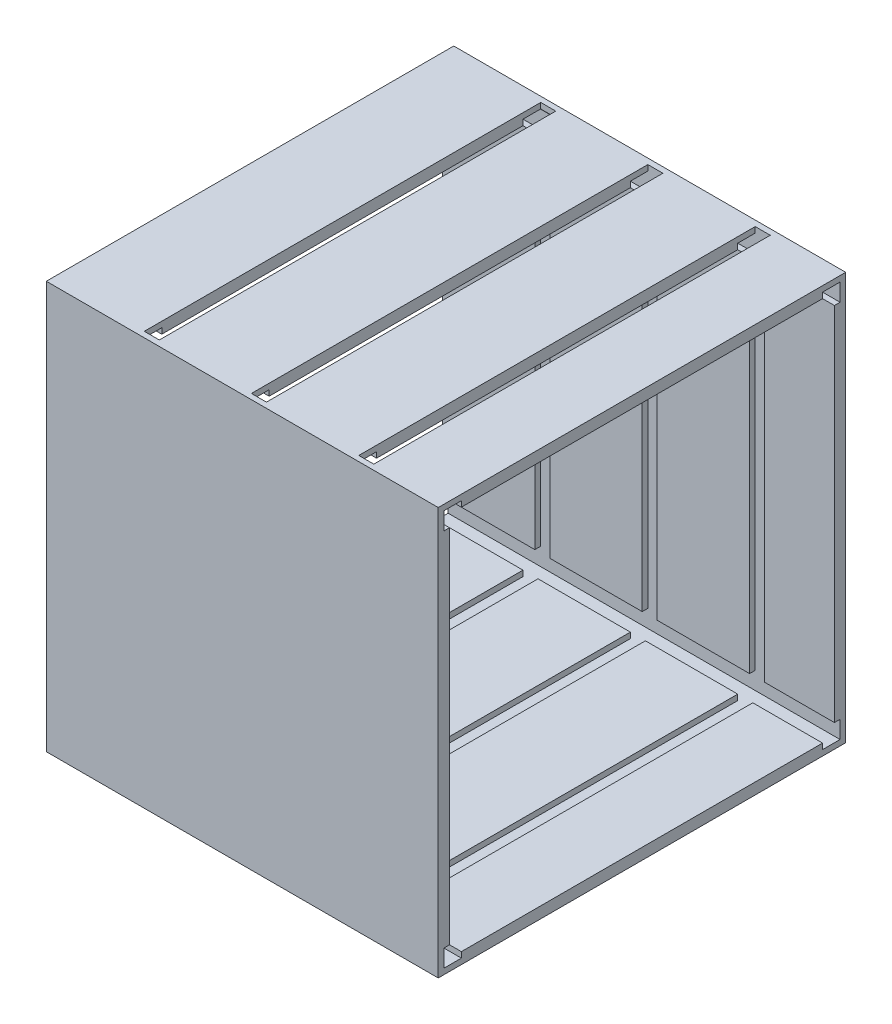
SolidWorks part; units mm, degrees
ref_plane "Front Plane" through (0, 0, 0) normal (0, 0, 1) x (1, 0, 0)
ref_plane "Top Plane" through (0, 0, 0) normal (0, 1, 0) x (1, 0, 0)
ref_plane "Right Plane" through (0, 0, 0) normal (1, 0, 0) x (0, 0, -1)
sketch "Sketch1" plane through (0, 0, 0) normal (1, 0, 0) x (0, 0, -1)
  line L1 (0, 0) -> (688.1, 0)
  line L2 (0, 0) -> (0, 688.1)
  line L3 (0, 688.1) -> (688.1, 688.1)
  line L4 (688.1, 0) -> (688.1, 688.1)
  line L5 (0, 0) -> (19.05, 0) construction
  line L6 (0, 0) -> (0, 19.05) construction
  line L7 (0, 19.05) -> (19.05, 19.05) construction
  line L8 (19.05, 0) -> (19.05, 19.05) construction
  line L9 (19.05, 19.05) -> (669.05, 19.05)
  line L10 (19.05, 19.05) -> (19.05, 669.05)
  line L11 (19.05, 669.05) -> (669.05, 669.05)
  line L12 (669.05, 19.05) -> (669.05, 669.05)
  dimension "D1" = 688.1
  dimension "D2" = 688.1
  dimension "D3" = 19.05
  dimension "D4" = 19.05
  dimension "D5" = 650
  dimension "D6" = 650
extrude "Boss-Extrude1" add sketch "Sketch1" along normal blind 661.9 contours L10 L11 L12 L9 | L2 L3 L4 L1
sketch "Sketch3" plane through (0, 0, -669.05) normal (0, 0, 1) x (1, 0, 0)
  line L1 (0, 669.05) -> (155.95, 669.05) construction
  line L2 (0, 669.05) -> (0, 19.05) construction
  line L3 (0, 19.05) -> (155.95, 19.05) construction
  line L4 (155.95, 669.05) -> (155.95, 19.05) construction
  line L5 (155.95, 669.05) -> (181.35, 669.05)
  line L6 (155.95, 669.05) -> (155.95, 19.05)
  line L7 (155.95, 19.05) -> (181.35, 19.05)
  line L8 (181.35, 669.05) -> (181.35, 19.05)
  line L9 (337.3, 669.05) -> (362.7, 669.05)
  line L10 (337.3, 669.05) -> (337.3, 19.05)
  line L11 (337.3, 19.05) -> (362.7, 19.05)
  line L12 (362.7, 669.05) -> (362.7, 19.05)
  line L13 (518.65, 669.05) -> (544.05, 669.05)
  line L14 (518.65, 669.05) -> (518.65, 19.05)
  line L15 (518.65, 19.05) -> (544.05, 19.05)
  line L16 (544.05, 669.05) -> (544.05, 19.05)
  line L17 (661.9, 688.1) -> (0, 688.1) construction
  point P15 (350, 669.05)
  dimension "D1" = 155.95
  dimension "D2" = 650
  dimension "D3" = 25.4
  dimension "D4" = 25.4
  dimension "D5" = 650
  dimension "D6" = 155.95
  dimension "D7" = 25.4
  dimension "D8" = 650
  dimension "D9" = 155.95
  dimension "D10" = 19.05
  dimension "D11" = 19.05
extrude "Cut-Extrude1" cut sketch "Sketch3" against normal blind 9.525
ref_plane "Plane1" through (0, 0, -344.05) normal (0, 0, -1) x (-1, 0, 0)
mirror "Mirror2" about plane through (0, 0, -344.05) normal (0, 0, -1) of "Cut-Extrude1"
ref_plane "Plane2" through (0, 344.05, 0) normal (0, 1, 0) x (1, 0, 0)
sketch "Sketch4" plane through (0, 19.05, 0) normal (0, 1, 0) x (1, 0, 0)
  line L0 (661.9, 688.1) -> (0, 688.1) construction
  line L1 (155.95, 678.575) -> (181.35, 678.575)
  line L2 (155.95, 678.575) -> (155.95, 9.075)
  line L3 (155.95, 9.075) -> (181.35, 9.075)
  line L4 (181.35, 678.575) -> (181.35, 9.075)
  line L5 (0, 0) -> (0, 688.1) construction
  line L6 (661.9, 0) -> (0, 0) construction
  line L7 (337.3, 678.575) -> (362.7, 678.575)
  line L8 (337.3, 678.575) -> (337.3, 9.075)
  line L9 (337.3, 9.075) -> (362.7, 9.075)
  line L10 (362.7, 678.575) -> (362.7, 9.075)
  line L11 (518.65, 678.575) -> (544.05, 678.575)
  line L12 (518.65, 678.575) -> (518.65, 9.525)
  line L13 (518.65, 9.525) -> (544.05, 9.525)
  line L14 (544.05, 678.575) -> (544.05, 9.525)
  dimension "D1" = 25.4
  dimension "D2" = 669.5
  dimension "D3" = 9.525
  dimension "D4" = 155.95
  dimension "D5" = 669.5
  dimension "D6" = 25.4
  dimension "D7" = 9.525
  dimension "D8" = 155.95
  dimension "D9" = 25.4
  dimension "D10" = 155.95
  dimension "D11" = 9.525
  dimension "D12" = 9.525
extrude "Cut-Extrude3" cut sketch "Sketch4" against normal blind 9.525
mirror "Mirror4" about plane through (0, 344.05, 0) normal (0, 1, 0) of "Cut-Extrude3"
sketch "Sketch6" plane through (0, 688.1, 0) normal (0, 1, 0) x (1, 0, 0)
  line L0 (0, 0) -> (0, 688.1) construction
  line L1 (155.95, 679.025) -> (181.35, 679.025)
  line L2 (155.95, 679.025) -> (155.95, 9.525)
  line L3 (155.95, 9.525) -> (181.35, 9.525)
  line L4 (181.35, 679.025) -> (181.35, 9.525)
  line L5 (337.3, 678.575) -> (362.7, 678.575)
  line L6 (337.3, 678.575) -> (337.3, 9.075)
  line L7 (337.3, 9.075) -> (362.7, 9.075)
  line L8 (362.7, 678.575) -> (362.7, 9.075)
  line L9 (518.65, 678.575) -> (544.05, 678.575)
  line L10 (518.65, 678.575) -> (518.65, 9.075)
  line L11 (518.65, 9.075) -> (544.05, 9.075)
  line L12 (544.05, 678.575) -> (544.05, 9.075)
  line L13 (661.9, 0) -> (0, 0) construction
  line L14 (661.9, 688.1) -> (0, 688.1) construction
  dimension "D1" = 669.5
  dimension "D2" = 25.4
  dimension "D3" = 155.95
  dimension "D4" = 9.525
  dimension "D5" = 25.4
  dimension "D6" = 669.5
  dimension "D7" = 9.525
  dimension "D8" = 155.95
  dimension "D9" = 25.4
  dimension "D10" = 669.5
  dimension "D11" = 9.525
  dimension "D12" = 155.95
extrude "Cut-Extrude4" cut sketch "Sketch6" against normal blind 9.525
sketch "Sketch7" plane through (0, 0, 0) normal (-1, 0, 0) x (0, 0, 1)
  line L0 (-19.05, 39.05) -> (-9.525, 39.05)
  line L1 (-19.05, 19.05) -> (-19.05, 669.05) construction
  line L2 (-9.525, 39.05) -> (-9.525, 9.525)
  line L3 (-9.525, 9.525) -> (-39.05, 9.525)
  line L4 (-39.05, 9.525) -> (-39.05, 19.05)
  line L5 (-19.05, 19.05) -> (-669.05, 19.05) construction
  line L6 (-39.05, 19.05) -> (-19.05, 19.05)
  line L7 (-19.05, 19.05) -> (-19.05, 39.05)
  dimension "D1" = 9.525
  dimension "D2" = 20
  dimension "D3" = 20
  dimension "D4" = 9.525
extrude "Cut-Extrude5" cut sketch "Sketch7" against normal blind 700
mirror "Mirror5" about plane through (0, 0, -344.05) normal (0, 0, -1) of "Cut-Extrude5"
mirror "Mirror6" about plane through (0, 344.05, 0) normal (0, 1, 0) of "Mirror5", "Cut-Extrude5"
